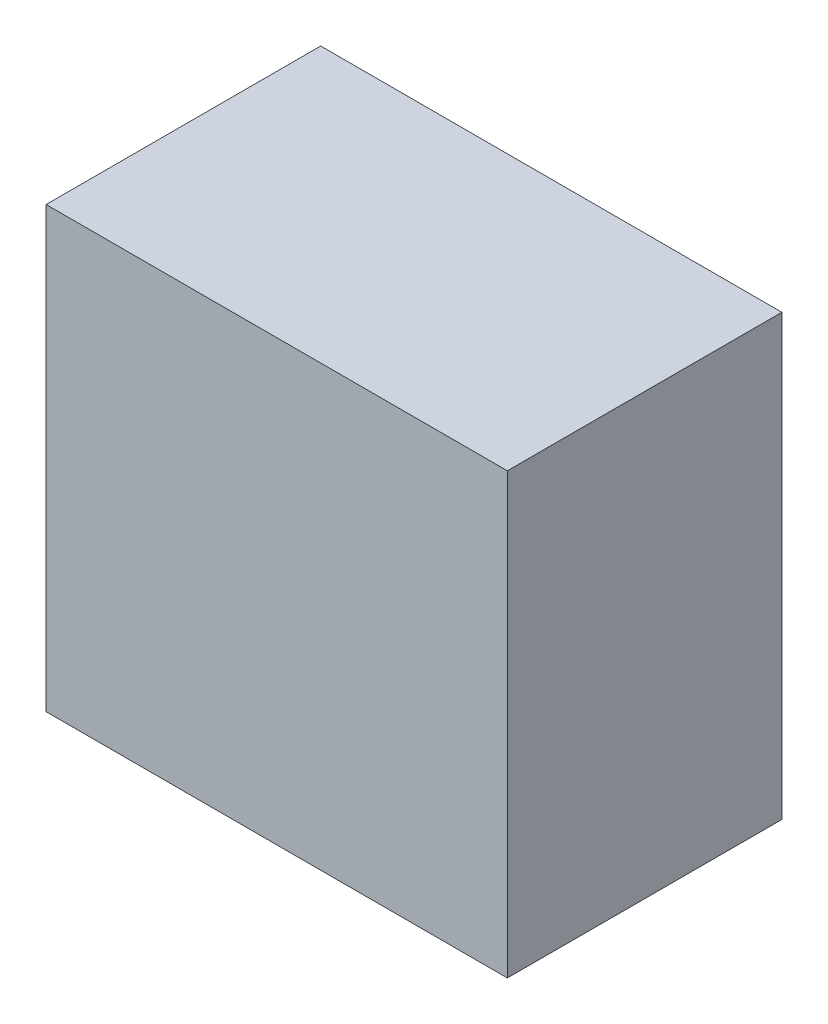
SolidWorks part; units mm, degrees
ref_plane "Front Plane" through (0, 0, 0) normal (0, 0, 1) x (1, 0, 0)
ref_plane "Top Plane" through (0, 0, 0) normal (0, 1, 0) x (1, 0, 0)
ref_plane "Right Plane" through (0, 0, 0) normal (1, 0, 0) x (0, 0, -1)
sketch "Sketch1" plane through (0, 0, 0) normal (0, 1, 0) x (1, 0, 0)
  line L1 (42, -25) -> (-42, -25)
  line L2 (42, -25) -> (42, 25)
  line L3 (42, 25) -> (-42, 25)
  line L4 (-42, -25) -> (-42, 25)
  line L5 (42, -25) -> (-42, 25) construction
  line L6 (42, 25) -> (-42, -25) construction
  point P0 (0, 0)
  dimension "D1" = 50
  dimension "D2" = 84
extrude "Boss-Extrude1" add sketch "Sketch1" along normal blind 80
